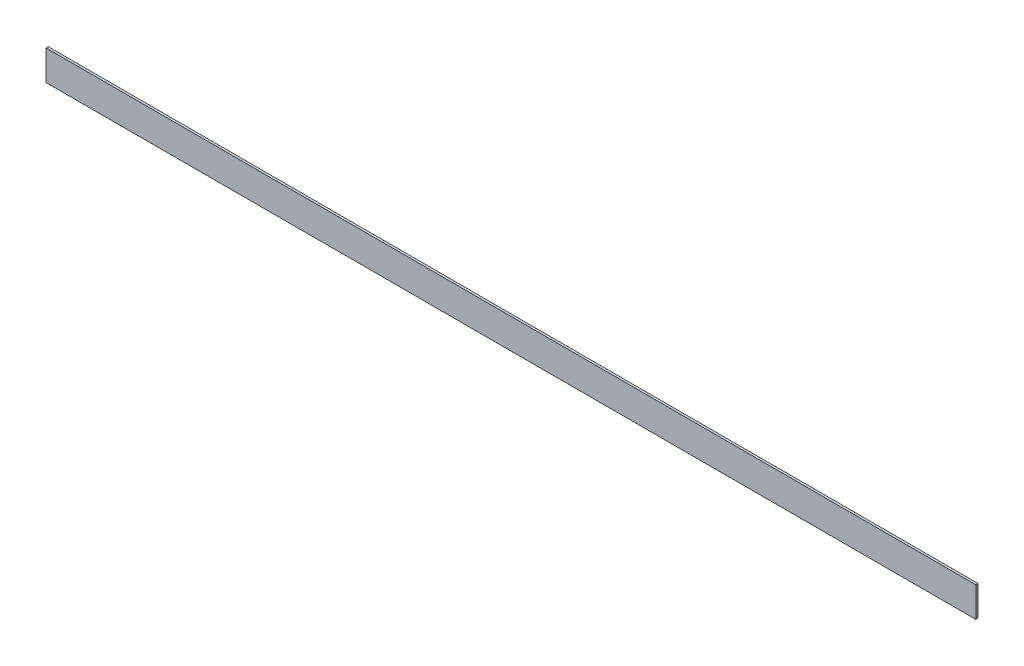
SolidWorks part; units mm, degrees
ref_plane "Front Plane" through (0, 0, 0) normal (0, 0, 1) x (1, 0, 0)
ref_plane "Top Plane" through (0, 0, 0) normal (0, 1, 0) x (1, 0, 0)
ref_plane "Right Plane" through (0, 0, 0) normal (1, 0, 0) x (0, 0, -1)
other "Configuration Table"
sketch "Sketch1" plane through (0, 0, 0) normal (0, 0, 1) x (1, 0, 0)
  line L1 (40, 1052) -> (660, 1052)
  line L2 (40, 1052) -> (40, 1072)
  line L3 (40, 1072) -> (660, 1072)
  line L4 (660, 1052) -> (660, 1072)
extrude "PRESS_tepsi_rafi_raf_buk_on_1" add sketch "Sketch1" against normal blind 1.5 from offset 20 separate body
